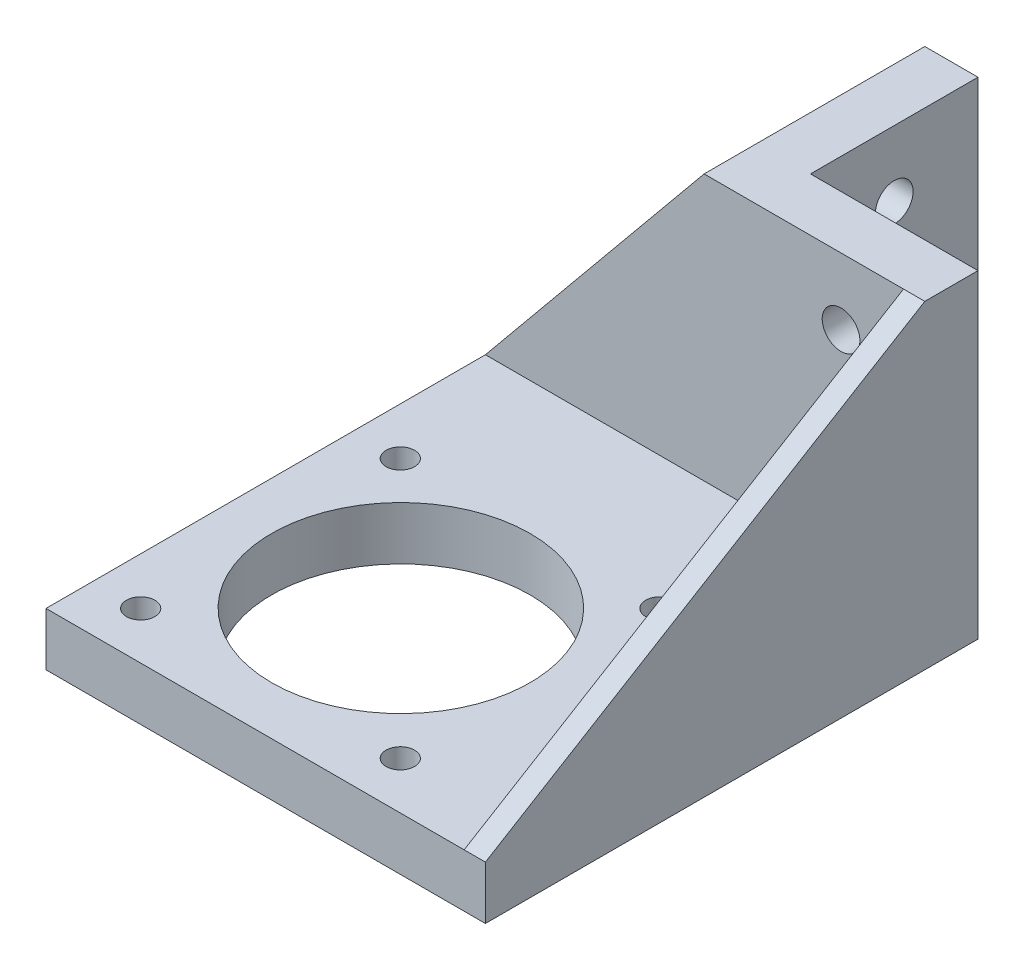
SolidWorks part; units mm, degrees
ref_plane "Front Plane" through (0, 0, 0) normal (0, 0, 1) x (1, 0, 0)
ref_plane "Top Plane" through (0, 0, 0) normal (0, 1, 0) x (1, 0, 0)
ref_plane "Right Plane" through (0, 0, 0) normal (1, 0, 0) x (0, 0, -1)
sketch "Sketch1" plane through (0, 0, 0) normal (0, 1, 0) x (1, 0, 0)
  line L1 (0, 0) -> (20, 0)
  line L2 (0, 0) -> (0, -6.35)
  line L3 (0, -6.35) -> (20, -6.35)
  line L4 (20, 0) -> (20, -6.35)
  line L5 (0, 0) -> (-6.35, 0)
  line L6 (0, 0) -> (0, 20)
  line L7 (0, 20) -> (-6.35, 20)
  line L8 (-6.35, 0) -> (-6.35, 20)
  line L9 (-6.35, 0) -> (0, 0)
  line L10 (-6.35, 0) -> (-6.35, -6.35)
  line L11 (-6.35, -6.35) -> (0, -6.35)
  line L12 (0, 0) -> (0, -6.35)
  dimension "D2" = 6.35
  dimension "D3" = 20
  dimension "D4" = 20
extrude "Boss-Extrude1" add sketch "Sketch1" along normal blind 38.1 contours L4 L1 L2 L3 | L10 L11 L2 L5 | L8 L5 L6 L7
sketch "Sketch2" plane through (0, 0, 0) normal (0, -1, 0) x (1, 0, 0)
  line L1 (20, 6.35) -> (-22.3, 6.35)
  line L2 (20, 6.35) -> (20, 48.65)
  line L3 (20, 48.65) -> (-22.3, 48.65)
  line L4 (-22.3, 6.35) -> (-22.3, 48.65)
  line L5 (-22.3, 6.35) -> (-6.35, 6.35)
  line L6 (-22.3, 6.35) -> (-22.3, -20)
  line L7 (-22.3, -20) -> (-6.35, -20)
  line L8 (-6.35, 6.35) -> (-6.35, -20)
  line L9 (-22.3, 48.65) -> (20, 48.65)
  line L10 (-22.3, 48.65) -> (-22.3, 58.81)
  line L11 (-22.3, 58.81) -> (20, 58.81)
  line L12 (20, 48.65) -> (20, 58.81)
  line L13 (-22.3, 6.35) -> (-32.46, 6.35)
  line L14 (-22.3, 6.35) -> (-22.3, 58.81)
  line L15 (-22.3, 58.81) -> (-32.46, 58.81)
  line L16 (-32.46, 6.35) -> (-32.46, 58.81)
  line M8 (20, 6.35) -> (-6.35, 6.35)
  line M9 (-6.35, 6.35) -> (-6.35, -20)
  dimension "D1" = 42.3
  dimension "D2" = 42.3
  dimension "D3" = 10.16
  dimension "D4" = 10.16
extrude "Boss-Extrude3" add sketch "Sketch2" against normal blind 6.35 contours L4 L1 L2 L3 M8 | L3 L12 L11 L10 | L6 L7 L1 M9 | L14 L13 L16 L15
sketch "Sketch3" plane through (0, 6.35, 0) normal (0, 1, 0) x (1, 0, 0)
  line L0 (-32.46, -6.35) -> (-32.46, -58.81) construction
  line L1 (9.84, -58.81) -> (-32.46, -58.81)
  line L2 (9.84, -58.81) -> (9.84, -16.51)
  line L3 (9.84, -16.51) -> (-32.46, -16.51)
  line L4 (-32.46, -58.81) -> (-32.46, -16.51)
  circle A0 centre (4.19, -22.16) radius 1.7
  circle A1 centre (4.19, -53.16) radius 1.7
  circle A2 centre (-26.81, -53.16) radius 1.7
  circle A3 centre (-26.81, -22.16) radius 1.7
  circle A4 centre (-11.3143, -37.592) radius 15.432
  point P6 (0, 0)
  point P7 (-11.31, -37.66)
  point P13 (4.19, -22.16)
  point P14 (4.19, -53.16)
  point P15 (-26.81, -53.16)
  point P16 (-26.81, -22.16)
  dimension "D3" = 3.4
  dimension "D1" = 42.3
  dimension "D2" = 31
  dimension "D4" = 0
extrude "Cut-Extrude1" cut sketch "Sketch3" against normal blind 6.35 contours A0 | A2 | A3 | A4 | A1
sketch "Sketch5" plane through (20, 0, 0) normal (1, 0, 0) x (0, 0, -1)
  line L0 (-6.35, 38.1) -> (-58.81, 6.35)
  line L1 (-58.81, 6.35) -> (-6.35, 6.35)
  line L2 (-6.35, 6.35) -> (-6.35, 38.1)
extrude "Boss-Extrude5" add sketch "Sketch5" against normal blind 2.54 contours L2 L0 L1
sketch "Sketch6" plane through (0, 6.35, 0) normal (0, 1, 0) x (1, 0, 0)
  line L1 (-22.3, 20) -> (-32.46, 20)
  line L2 (-22.3, 20) -> (-22.3, -6.35)
  line L3 (-22.3, -6.35) -> (-32.46, -6.35)
  line L4 (-32.46, 20) -> (-32.46, -6.35)
extrude "Boss-Extrude6" add sketch "Sketch6" against normal up to surface (6.35 mm away) up to face at (-26.81, 0, 54.86)
sketch "Sketch7" plane through (0, 0, -20) normal (0, 0, -1) x (-1, 0, 0)
  line L0 (6.35, 38.1) -> (32.46, 6.35)
  line L1 (32.46, 6.35) -> (6.35, 6.35)
  line L2 (6.35, 6.35) -> (6.35, 38.1)
extrude "Boss-Extrude7" add sketch "Sketch7" against normal blind 2.54
sketch "Sketch8" plane through (0, 0, 6.35) normal (0, 0, 1) x (1, 0, 0)
  line L0 (-6.35, 38.1) -> (-32.46, 6.35)
  line L1 (-32.46, 6.35) -> (-6.35, 6.35)
  line L2 (-6.35, 6.35) -> (-6.35, 38.1)
extrude "Boss-Extrude8" add sketch "Sketch8" against normal blind 2.54
sketch "Sketch9" plane through (-6.35, 0, 0) normal (-1, 0, 0) x (0, 0, 1)
  line L0 (3.81, 6.35) -> (-17.46, 6.35) construction
  line L3 (-20, 38.1) -> (0, 38.1)
  line L6 (-20, 38.1) -> (-20, 6.35)
  line L8 (-20, 6.35) -> (0, 6.35)
  line L9 (0, 38.1) -> (0, 6.35)
  line L10 (0, 22.225) -> (-20, 22.225)
  line L11 (-20, 22.225) -> (-10, 22.225)
  line L12 (-10, 22.225) -> (-10, 38.1)
  line L13 (-10, 22.225) -> (-10, 6.35)
  point P9 (-10, 14.2875)
  point P13 (-10, 30.1625)
  dimension "D1" = 20
hole_wizard "M4 Clearance Hole2" positions "Sketch12" profile "Sketch13" hole size "M4" standard "ANSI Metric" end condition through all
sketch "Sketch12" plane through (-6.35, 0, 0) normal (-1, 0, 0) x (0, 0, 1)
  point P0 (-10, 30.1625)
  point P3 (-10, 14.2875)
sketch "Sketch13" plane through (-6.35, 30.1625, -10) normal (0, 1, 0) x (0, 0, 1)
  line L0 (0, 0) -> (0, 26.35)
  line L1 (0, 26.35) -> (2.25, 26.35)
  line L2 (2.25, 26.35) -> (2.25, 0)
  line L5 (2.25, 0) -> (0, 0)
  line L11 (0, -6.35) -> (0, 107.95) construction
  dimension "Thru Hole Dia." = 4.5
  dimension "Thru Hole Depth" = 26.35
sketch "Sketch14" plane through (0, 0, 6.35) normal (0, 0, 1) x (1, 0, 0)
  line L0 (17.46, 6.35) -> (-32.46, 6.35) construction
  line L1 (20, 38.1) -> (0, 38.1)
  line L2 (20, 38.1) -> (20, 6.35)
  line L3 (20, 6.35) -> (0, 6.35)
  line L4 (0, 38.1) -> (0, 6.35)
  line L5 (20, 22.225) -> (0, 22.225)
  line L6 (10, 22.225) -> (10, 6.35)
  line L7 (10, 38.1) -> (10, 22.225)
  point P12 (10, 30.1625)
  point P13 (10, 14.2875)
  dimension "D1" = 20
hole_wizard "M4 Clearance Hole3" positions "Sketch15" profile "Sketch16" hole size "M4" standard "ANSI Metric" end condition through all
sketch "Sketch15" plane through (0, 0, 6.35) normal (0, 0, 1) x (1, 0, 0)
  point P0 (10, 30.1625)
  point P3 (10, 14.2875)
sketch "Sketch16" plane through (10, 30.1625, 6.35) normal (1, 0, 0) x (0, -1, 0)
  line L0 (0, 0) -> (0, 26.35)
  line L1 (0, 26.35) -> (2.25, 26.35)
  line L2 (2.25, 26.35) -> (2.25, 0)
  line L5 (2.25, 0) -> (0, 0)
  line L11 (0, -6.35) -> (0, 107.95) construction
  dimension "Thru Hole Dia." = 4.5
  dimension "Thru Hole Depth" = 26.35
